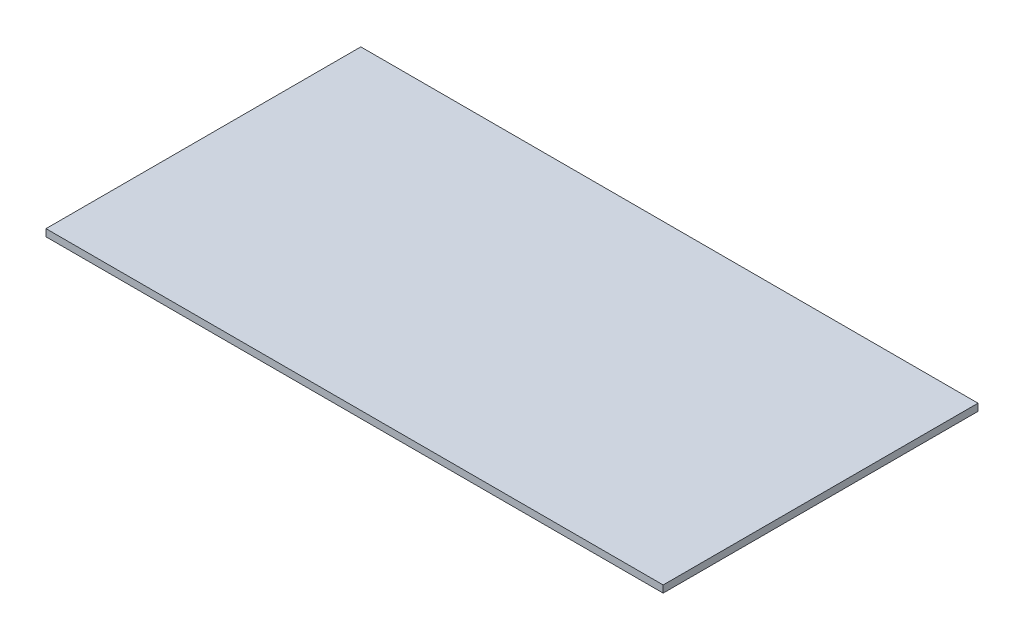
SolidWorks part; units mm, degrees
ref_plane "Front Plane" through (0, 0, 0) normal (0, 0, 1) x (1, 0, 0)
ref_plane "Top Plane" through (0, 0, 0) normal (0, 1, 0) x (1, 0, 0)
ref_plane "Right Plane" through (0, 0, 0) normal (1, 0, 0) x (0, 0, -1)
sketch "Sketch1" plane through (0, 0, 0) normal (0, 1, 0) x (1, 0, 0)
  line L1 (0, 0) -> (143.4611, 0)
  line L2 (0, 0) -> (0, 73.182)
  line L3 (0, 73.182) -> (143.4611, 73.182)
  line L4 (143.4611, 0) -> (143.4611, 73.182)
extrude "Boss-Extrude1" add sketch "Sketch1" along normal blind 1.651
